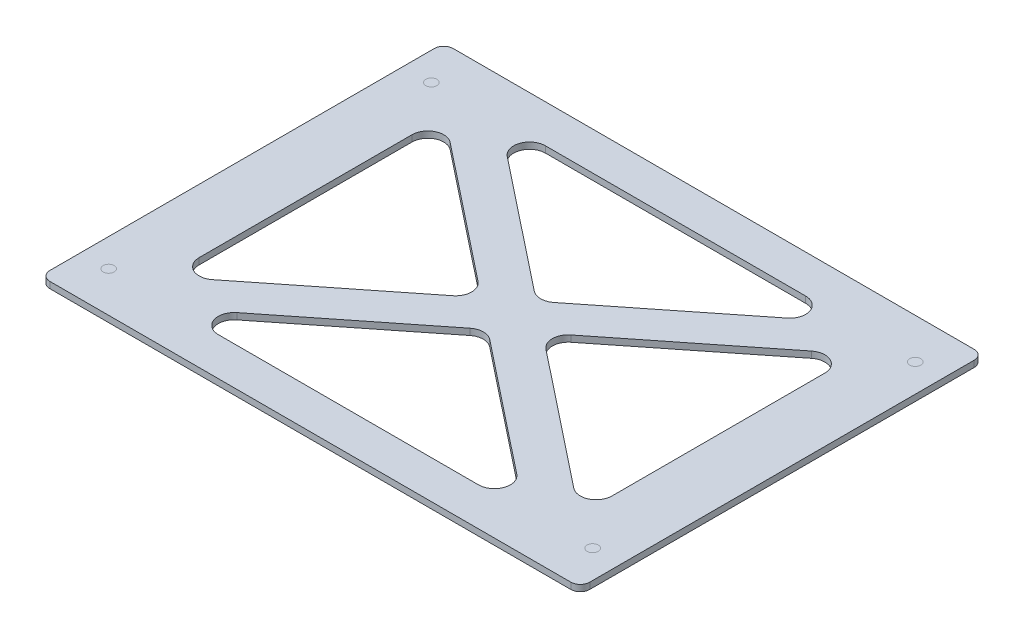
SolidWorks part; units mm, degrees
ref_plane "Front Plane" through (0, 0, 0) normal (0, 0, 1) x (1, 0, 0)
ref_plane "Top Plane" through (0, 0, 0) normal (0, 1, 0) x (1, 0, 0)
ref_plane "Right Plane" through (0, 0, 0) normal (1, 0, 0) x (0, 0, -1)
sketch "Sketch1" plane through (0, 0, 0) normal (0, 1, 0) x (1, 0, 0)
  line L1 (-84.2086, 56.5444) -> (85.7914, 56.5444)
  line L2 (-84.2086, 56.5444) -> (-84.2086, -70.4556)
  line L3 (-84.2086, -70.4556) -> (85.7914, -70.4556)
  line L4 (85.7914, 56.5444) -> (85.7914, -70.4556)
  line L5 (-54.5469, 44.5444) -> (56.1298, 44.5444)
  line L6 (-64.2086, 36.8894) -> (-64.2086, -50.8006)
  line L7 (-54.5469, -58.4556) -> (56.1298, -58.4556)
  line L8 (65.7914, 36.8894) -> (65.7914, -50.8006)
  line L10 (-64.2086, 36.8894) -> (-8.8702, -6.9556)
  line L11 (-54.5469, 44.5444) -> (0.7914, 0.6994)
  line L12 (56.1298, 44.5444) -> (0.7914, 0.6994)
  line L13 (65.7914, 36.8894) -> (10.4531, -6.9556)
  line L14 (10.4531, -6.9556) -> (65.7914, -50.8006)
  line L15 (0.7914, -14.6106) -> (56.1298, -58.4556)
  line L16 (0.7914, -14.6106) -> (-54.5469, -58.4556)
  line L17 (-8.8702, -6.9556) -> (-64.2086, -50.8006)
  dimension "D1" = 170
  dimension "D2" = 127
  dimension "D3" = 12
  dimension "D4" = 12
  dimension "D5" = 20
  dimension "D6" = 20
extrude "Boss-Extrude1" add sketch "Sketch1" along normal blind 2
fillet "Fillet1" radius 5 11 edges at (-8.8702, 1, 6.9556) (10.4531, 1, 6.9556) (0.7914, 1, 14.6106) (0.7914, 1, -0.6994) (56.1298, 1, 58.4556) (65.7914, 1, 50.8006) (65.7914, 1, -36.8894) (-64.2086, 1, 50.8006) (-64.2086, 1, -36.8894) (56.1298, 1, -44.5444) (-54.5469, 1, -44.5444)
fillet "Fillet2" radius 3 4 edges at (-84.2086, 1, 70.4556) (85.7914, 1, 70.4556) (85.7914, 1, -56.5444) (-84.2086, 1, -56.5444)
sketch "Sketch2" plane through (0, 2, 0) normal (0, 1, 0) x (1, 0, 0)
  line L0 (-84.2086, 53.5444) -> (-84.2086, -67.4556) construction
  line L1 (82.7914, 56.5444) -> (-81.2086, 56.5444) construction
  circle A0 centre (-75.4086, 43.8444) radius 1.75
  circle A1 centre (76.9914, 43.8444) radius 1.75
  circle A2 centre (76.9914, -57.7556) radius 1.75
  circle A3 centre (-75.4086, -57.7556) radius 1.75
  dimension "D1" = 3.5
  dimension "D2" = 3.5
  dimension "D3" = 3.5
  dimension "D4" = 3.5
  dimension "D5" = 152.4
  dimension "D6" = 152.4
  dimension "D7" = 101.6
  dimension "D8" = 101.6
  dimension "D9" = 8.8
  dimension "D10" = 12.7
extrude "Cut-Extrude1" cut sketch "Sketch2" against normal blind 0.001
fillet "Fillet3" radius 5 1 edges at (-54.5469, 1, 58.4556)
